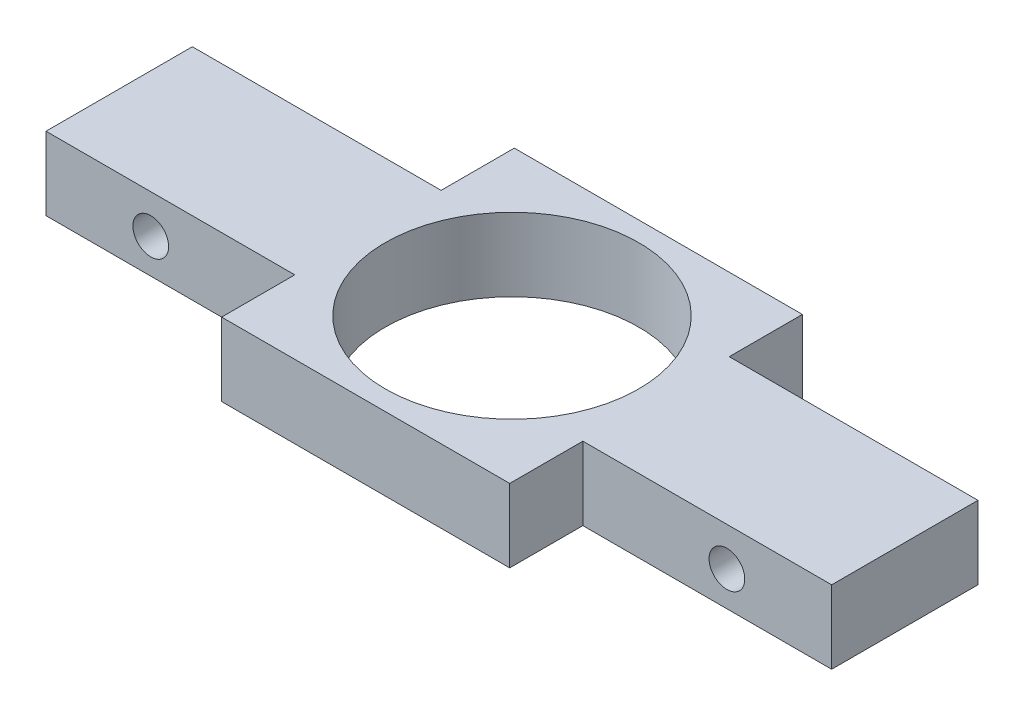
SolidWorks part; units mm, degrees
ref_plane "Front Plane" through (0, 0, 0) normal (0, 0, 1) x (1, 0, 0)
ref_plane "Top Plane" through (0, 0, 0) normal (0, 1, 0) x (1, 0, 0)
ref_plane "Right Plane" through (0, 0, 0) normal (1, 0, 0) x (0, 0, -1)
sketch "Sketch1" plane through (0, 0, 0) normal (0, 1, 0) x (1, 0, 0)
  line L0 (-34.09, 6.35) -> (-12.5, 6.35)
  line L1 (-12.5, 6.35) -> (-12.5, 12.7)
  line L2 (-12.5, 12.7) -> (12.5, 12.7)
  line L3 (12.5, 12.7) -> (12.5, 6.35)
  line L4 (12.5, 6.35) -> (34.09, 6.35)
  line L5 (-34.09, 6.35) -> (-34.09, -6.35)
  line L6 (-34.09, -6.35) -> (-12.5, -6.35)
  line L7 (-12.5, -6.35) -> (-12.5, -12.7)
  line L8 (-12.5, -12.7) -> (12.5, -12.7)
  line L9 (12.5, -12.7) -> (12.5, -6.35)
  line L10 (12.5, -6.35) -> (34.09, -6.35)
  line L11 (34.09, -6.35) -> (34.09, 6.35)
  line L12 (-12.5, 6.35) -> (12.5, -6.35) construction
  circle A0 centre (0, 0) radius 11
  dimension "D1" = 22
  dimension "D2" = 6.35
  dimension "D3" = 25
  dimension "D4" = 21.59
  dimension "D5" = 12.7
extrude "Boss-Extrude1" add sketch "Sketch1" along normal blind 6.35
sketch "Sketch2" plane through (0, 0, -6.35) normal (0, 0, -1) x (-1, 0, 0)
  line L0 (25, 3) -> (-25, 3) construction
  line L1 (0, 0) -> (0, 3) construction
  circle A0 centre (25, 3) radius 1.55
  circle A1 centre (-25, 3) radius 1.55
  dimension "D2" = 3.1
  dimension "D1" = 50
  dimension "D3" = 3
extrude "Cut-Extrude1" cut sketch "Sketch2" against normal through all both and the other way through all
